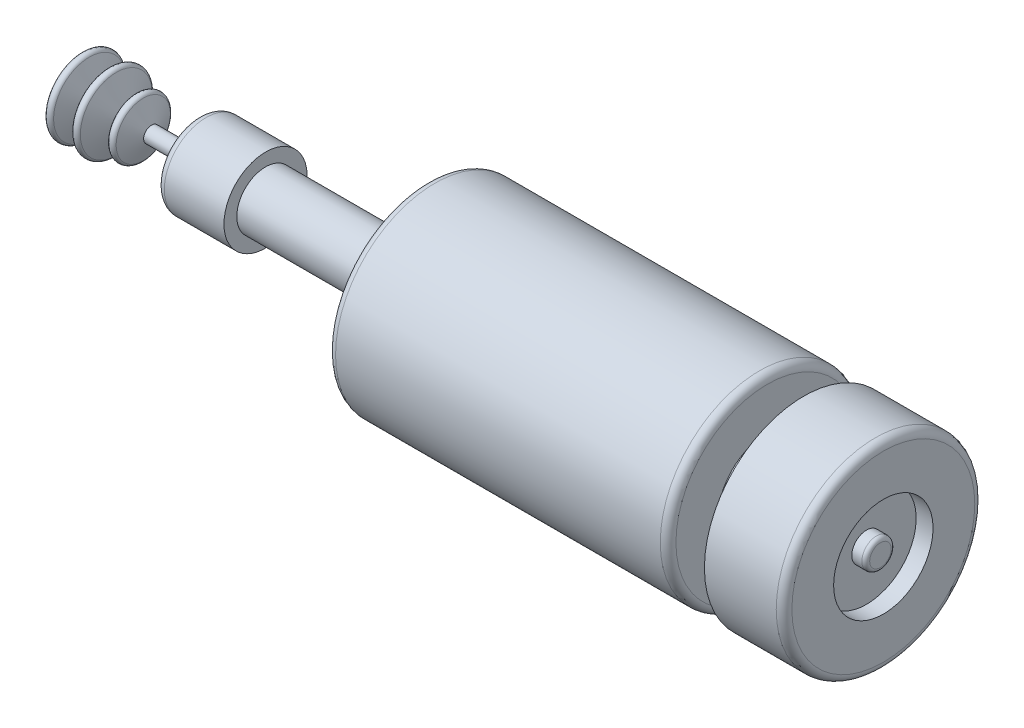
SolidWorks part; units mm, degrees
ref_plane "Plan de face" through (0, 0, 0) normal (0, 0, 1) x (1, 0, 0)
ref_plane "Plan de dessus" through (0, 0, 0) normal (0, 1, 0) x (1, 0, 0)
ref_plane "Plan de droite" through (0, 0, 0) normal (1, 0, 0) x (0, 0, -1)
sketch "Esquisse1" plane through (0, 0, 0) normal (0, 0, 1) x (1, 0, 0)
  line L0 (0, 0) -> (86.7614, 0)
  line L1 (0, 0) -> (-87.5, 0)
  line L2 (14.02, 157.1926) -> (514.02, 157.1926) construction
  line L3 (87.5, 12.6943) -> (87.5, 23.3547)
  line L4 (67.1587, 25.3547) -> (67.1587, 3.7416)
  line L5 (67.1587, 25.3547) -> (85.5, 25.3547)
  line L6 (87.5, 12.6943) -> (83.1927, 12.6943)
  line L7 (83.1927, 12.6943) -> (83.1927, 3.7416)
  line L8 (83.1927, 3.7416) -> (85.5, 3.7416)
  line L9 (85.5, 3.7416) -> (85.7614, 3.7416)
  line L10 (86.7614, 2.7416) -> (86.7614, 0)
  line L11 (67.1587, 3.7416) -> (66.701, 3.7416)
  line L12 (66.701, 3.7416) -> (66.701, 4.0721)
  line L13 (66.701, 4.0721) -> (63.9473, 4.0721)
  line L14 (63.9473, 4.0721) -> (63.9473, 12.6774)
  line L15 (63.9473, 12.6774) -> (57.887, 12.6774)
  line L16 (57.887, 12.6774) -> (57.887, 23.3547)
  line L17 (55.887, 25.3547) -> (-27.0483, 25.3547)
  line L18 (-29.0483, 23.3547) -> (-29.0483, 12.6774)
  line L19 (-29.0483, 12.6774) -> (-35.3619, 12.6774)
  line L20 (-35.3619, 12.6774) -> (-35.3619, 4.0721)
  line L21 (-35.3619, 4.0721) -> (-39.6476, 4.0721)
  line L22 (-39.6476, 4.0721) -> (-39.6476, 7.3508)
  line L23 (-39.6476, 7.3508) -> (-70.2778, 7.3508)
  line L24 (-70.2778, 7.3508) -> (-70.2778, 10.6281)
  line L25 (-70.2778, 10.6281) -> (-85.5, 10.6281)
  line L27 (-87.5, 2) -> (-99.4233, 2)
  line L28 (-117.5, 0) -> (-87.5, 0)
  line L29 (-99.4233, 2) -> (-101.5207, 6.9181)
  line L30 (-103.2749, 7.0772) -> (-105.8538, 3.1744)
  line L31 (-87.5, 8.6281) -> (-87.5, 2)
  line L32 (-105.8538, 3.1744) -> (-108.4119, 9.1728)
  line L33 (-110.1661, 9.3318) -> (-113.3324, 4.5402)
  line L34 (-113.3324, 4.5402) -> (-115.2879, 9.1258)
  line L35 (-117.1678, 9.0133) -> (-118.6077, 4.0721)
  line L36 (-118.6077, 4.0721) -> (-118.8766, 0)
  line L37 (-118.8766, 0) -> (-117.5, 0)
  arc A0 (87.5, 23.3547) -> (85.5, 25.3547) centre (85.5, 23.3547) ccw
  arc A1 (86.7614, 2.7416) -> (85.7614, 3.7416) centre (85.7614, 2.7416) ccw
  arc A2 (-85.5, 10.6281) -> (-87.5, 8.6281) centre (-85.5, 8.6281) ccw
  arc A3 (57.887, 23.3547) -> (55.887, 25.3547) centre (55.887, 23.3547) ccw
  arc A4 (-115.2879, 9.1258) -> (-117.1678, 9.0133) centre (-116.2078, 8.7335) ccw
  arc A5 (-29.0483, 23.3547) -> (-27.0483, 25.3547) centre (-27.0483, 23.3547) cw
  arc A6 (-110.1661, 9.3318) -> (-108.4119, 9.1728) centre (-109.3318, 8.7805) cw
  arc A7 (-101.5207, 6.9181) -> (-103.2749, 7.0772) centre (-102.4406, 6.5258) ccw
  dimension "D1" = 2
  dimension "D2" = 1
  dimension "D3" = 2
  dimension "D4" = 2
  dimension "D5" = 1
  dimension "D6" = 2
revolve "Révolution1" add sketch "Esquisse1" angle 360 about L0
